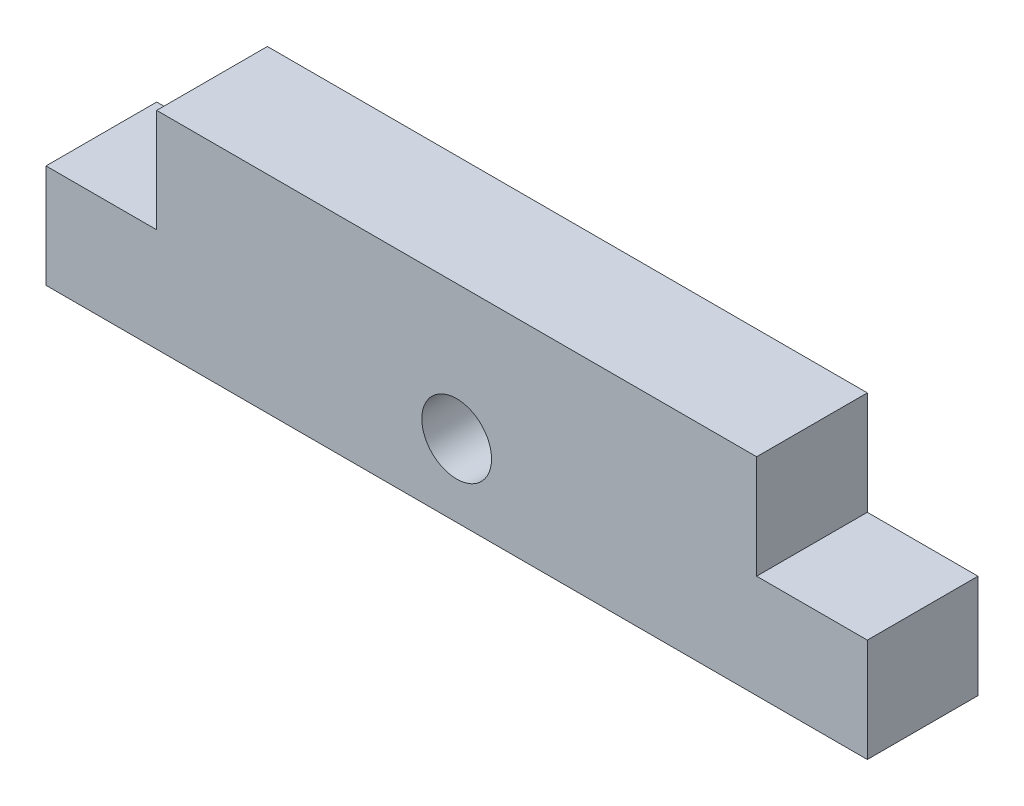
SolidWorks part; units mm, degrees
ref_plane "Front Plane" through (0, 0, 0) normal (0, 0, 1) x (1, 0, 0)
ref_plane "Top Plane" through (0, 0, 0) normal (0, 1, 0) x (1, 0, 0)
ref_plane "Right Plane" through (0, 0, 0) normal (1, 0, 0) x (0, 0, -1)
sketch "Model" plane through (0, 0, 0) normal (0, 0, 1) x (1, 0, 0)
  line L0 (0, 0) -> (0, 10) construction
  line L1 (-19.85, 0) -> (19.85, 0)
  line L2 (-19.85, 0) -> (-19.85, 5)
  line L3 (-14.5, 10) -> (14.5, 10)
  line L4 (19.85, 0) -> (19.85, 5)
  line L5 (19.85, 5) -> (14.5, 5)
  line L6 (14.5, 10) -> (14.5, 5)
  line L7 (-19.85, 5) -> (-14.5, 5)
  line L8 (-14.5, 10) -> (-14.5, 5)
  circle A0 centre (0, 3.5) radius 1.685
  dimension "D3" = 3.37
  dimension "D2" = 3.5
  dimension "D5" = 39.7
  dimension "D8" = 5.35
  dimension "D9" = 5
  dimension "D12" = 10
extrude "Boss-Extrude1" add sketch "Model" along normal blind 5.35
equation "\"mdfthick\"=5.35"
equation "\"D8@Model\"=\"mdfthick\""
equation "\"D1@Boss-Extrude1\"=\"mdfthick\""
